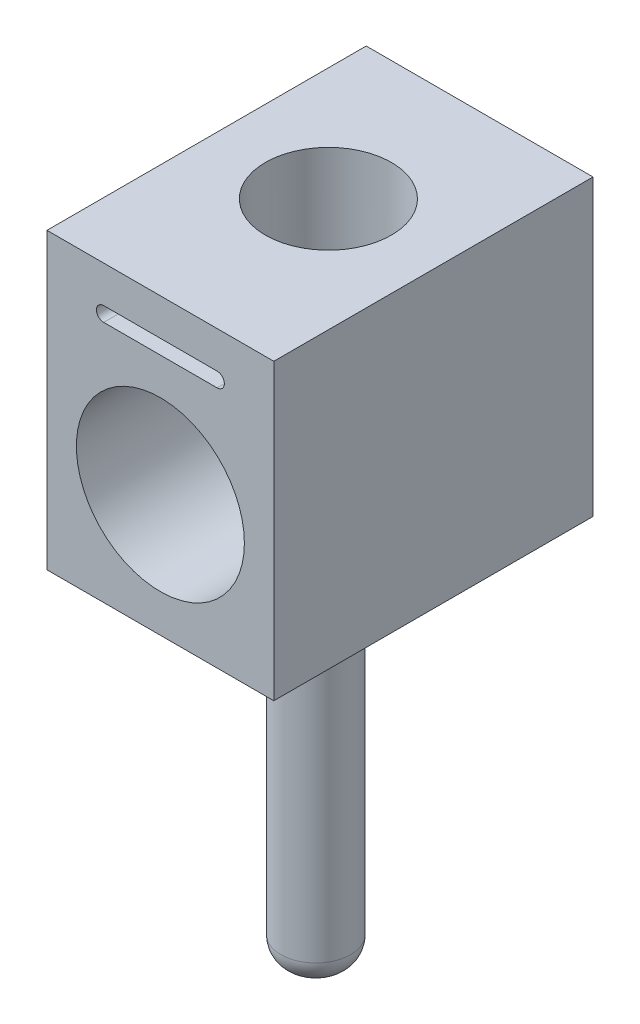
SolidWorks part; units mm, degrees
ref_plane "Спереди" through (0, 0, 0) normal (0, 0, 1) x (1, 0, 0)
ref_plane "Сверху" through (0, 0, 0) normal (0, 1, 0) x (1, 0, 0)
ref_plane "Справа" through (0, 0, 0) normal (1, 0, 0) x (0, 0, -1)
sketch "Эскиз1" plane through (0, 0, 0) normal (0, 0, 1) x (1, 0, 0)
  line L1 (-1.35, 1.75) -> (1.35, 1.75)
  line L2 (-1.35, 1.75) -> (-1.35, -1.75)
  line L3 (-1.35, -1.75) -> (1.35, -1.75)
  line L4 (1.35, 1.75) -> (1.35, -1.75)
  line L5 (-1.35, 1.75) -> (1.35, -1.75) construction
  line L6 (-1.35, -1.75) -> (1.35, 1.75) construction
  point P0 (0, 0)
  dimension "D1" = 2.7
  dimension "D2" = 3.5
extrude "Бобышка-Вытянуть1" add sketch "Эскиз1" against normal blind 3.8
sketch "Эскиз2" plane through (0, 0, 0) normal (0, 0, 1) x (1, 0, 0)
  line L0 (-1.35, -0.3) -> (1.35, -0.3) construction
  line L1 (0, 1.75) -> (0, -1.75) construction
  line L4 (1.35, -1.75) -> (1.35, 1.75)
  line L5 (1.35, 1.75) -> (-1.35, 1.75)
  line L6 (-1.35, 1.75) -> (-1.35, -1.75)
  line L7 (-1.35, -1.75) -> (1.35, -1.75)
  line L8 (1.35, -1.75) -> (1.35, 1.75)
  line L9 (1.35, 1.75) -> (-1.35, 1.75)
  line L10 (-1.35, 1.75) -> (-1.35, -1.75)
  line L11 (-1.35, -1.75) -> (1.35, -1.75)
  circle A0 centre (0, -0.3) radius 1
  dimension "D3" = 2
  dimension "D1" = 0
  dimension "D2" = 1.45
extrude "Вырез-Вытянуть1" cut sketch "Эскиз2" against normal through all flip side to cut
sketch "Эскиз4" plane through (0, 1.75, 0) normal (0, 1, 0) x (1, 0, 0)
  line L4 (-1.35, 0) -> (1.35, 0)
  line L5 (1.35, 0) -> (1.35, 3.8)
  line L6 (1.35, 3.8) -> (-1.35, 3.8)
  line L7 (-1.35, 3.8) -> (-1.35, 0)
  line L8 (-1.35, 0) -> (1.35, 0)
  line L9 (1.35, 0) -> (1.35, 3.8)
  line L10 (1.35, 3.8) -> (-1.35, 3.8)
  line L11 (-1.35, 3.8) -> (-1.35, 0)
  line L12 (-1.35, 2) -> (1.35, 2) construction
  circle A0 centre (0, 2) radius 0.75
  dimension "D3" = 1.5
  dimension "D1" = 0
  dimension "D2" = 2
extrude "Вырез-Вытянуть2" cut sketch "Эскиз4" against normal blind 1.85 flip side to cut
sketch "Эскиз5" plane through (0, 0, 0) normal (0, 0, 1) x (1, 0, 0)
  line L0 (0, 1.75) -> (0, 0.7) construction
  line L1 (1.35, 1.75) -> (-1.35, 1.75) construction
  line L2 (0, 1.225) -> (1.35, 1.225) construction
  line L3 (1.35, -1.75) -> (1.35, 1.75) construction
  line L4 (-0.675, 1.225) -> (0.675, 1.225) construction
  line L5 (-0.675, 1.3114) -> (0.675, 1.3114)
  line L6 (-0.675, 1.1386) -> (0.675, 1.1386)
  circle A0 centre (0, -0.3) radius 1 construction
  arc A1 (-0.675, 1.3114) -> (-0.675, 1.1386) centre (-0.675, 1.225) ccw
  arc A2 (0.675, 1.1386) -> (0.675, 1.3114) centre (0.675, 1.225) ccw
  point P13 (0, 1.225)
extrude "Вырез-Вытянуть3" cut sketch "Эскиз5" against normal blind 0.5
sketch "Эскиз6" plane through (0, -1.75, 0) normal (0, -1, 0) x (1, 0, 0)
  line L0 (0, 0) -> (0, -3.8) construction
  line L4 (-1.35, 0) -> (1.35, 0) construction
  line L5 (-1.35, -3.8) -> (1.35, -3.8) construction
  circle A0 centre (0, -1.85) radius 0.415
  dimension "D1" = 0.83
  dimension "D2" = 1.85
extrude "Бобышка-Вытянуть2" add sketch "Эскиз6" along normal blind 4.31
fillet "Скругление1" radius 0.3 1 edges at (0, -6.06, -2.265)
fillet "Скругление2" radius 0.1 1 edges at (0, -1.75, -2.265)
